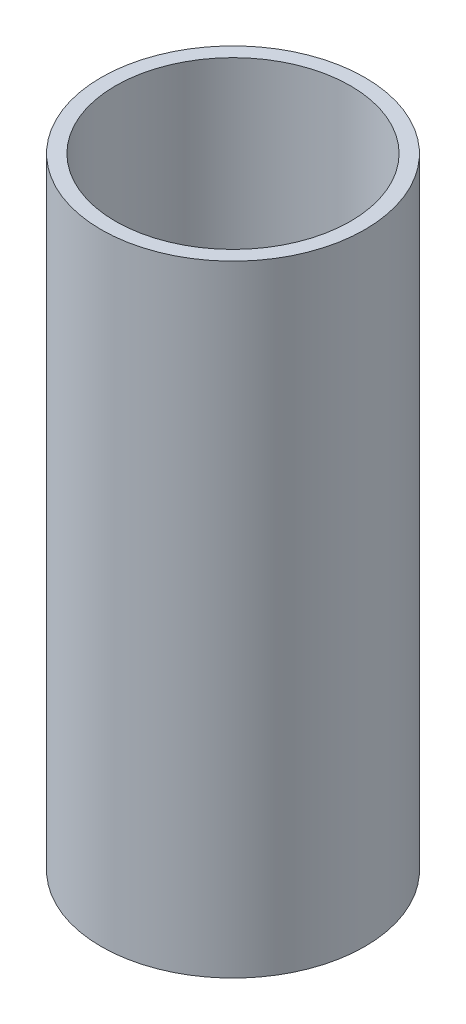
SolidWorks part; units mm, degrees
ref_plane "Front" through (0, 0, 0) normal (0, 0, 1) x (1, 0, 0)
ref_plane "Top" through (0, 0, 0) normal (0, 1, 0) x (1, 0, 0)
ref_plane "Right" through (0, 0, 0) normal (1, 0, 0) x (0, 0, -1)
sketch "Sketch1" plane through (0, 0, 0) normal (0, 1, 0) x (1, 0, 0)
  circle A0 centre (0, 0) radius 11
  circle A1 centre (0, 0) radius 9.8
  dimension "D1" = 22
  dimension "D2" = 1.2
extrude "Boss-Extrude1" add sketch "Sketch1" along normal blind 51.8
